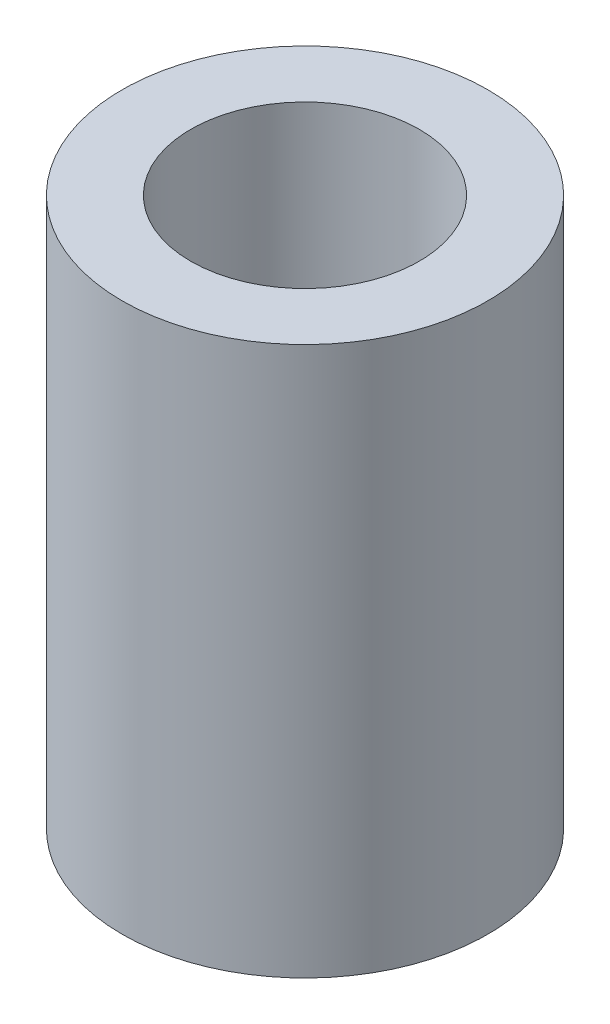
SolidWorks part; units mm, degrees
ref_plane "前视基准面" through (0, 0, 0) normal (0, 0, 1) x (1, 0, 0)
ref_plane "上视基准面" through (0, 0, 0) normal (0, 1, 0) x (1, 0, 0)
ref_plane "右视基准面" through (0, 0, 0) normal (1, 0, 0) x (0, 0, -1)
other "Configuration Table"
sketch "草图1" plane through (0, 0, 0) normal (0, 1, 0) x (1, 0, 0)
  circle A0 centre (0, 0) radius 5
  circle A1 centre (0, 0) radius 8
  dimension "D1" = 10
  dimension "D2" = 16
extrude "凸台-拉伸1" add sketch "草图1" along normal blind 24
